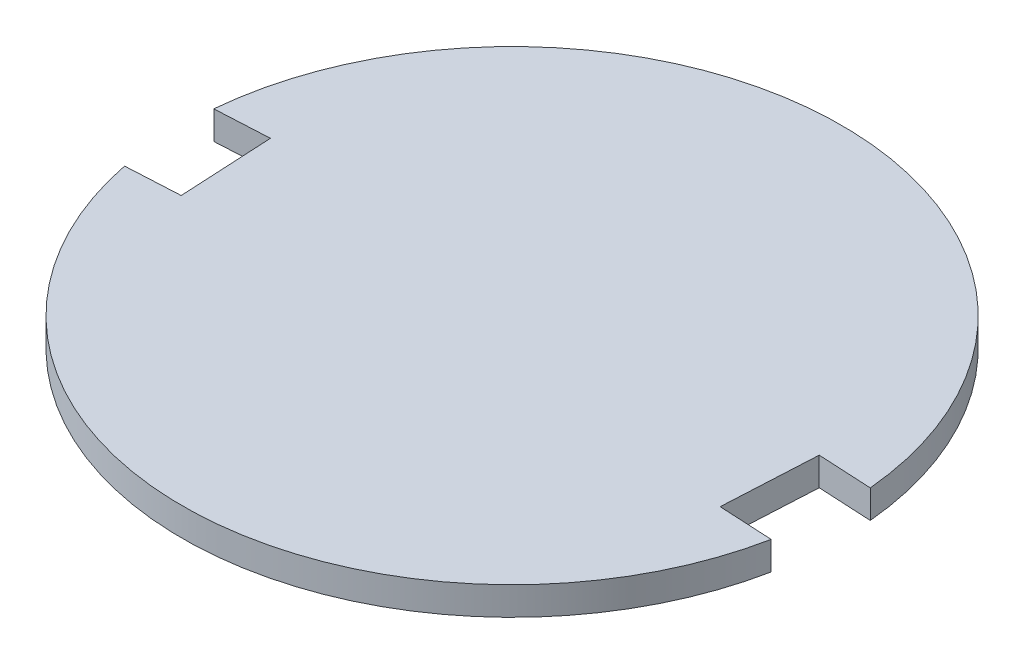
SolidWorks part; units mm, degrees
ref_plane "Спереди" through (0, 0, 0) normal (0, 0, 1) x (1, 0, 0)
ref_plane "Сверху" through (0, 0, 0) normal (0, 1, 0) x (1, 0, 0)
ref_plane "Справа" through (0, 0, 0) normal (1, 0, 0) x (0, 0, -1)
sketch "Эскиз1" plane through (0, 0, 0) normal (0, 1, 0) x (1, 0, 0)
  line L0 (-32.059, 10.3198) -> (-26.3445, 10.6193)
  line L1 (-26.3445, 10.6193) -> (-26.8686, 20.6193)
  line L2 (-26.8686, 20.6193) -> (-32.5851, 20.3197)
  line L3 (-32.6945, 17.1395) -> (-32.5029, 13.4847) construction
  line L4 (2.2701, 17.1395) -> (2.2701, 49.4493) construction
  line L5 (-32.5987, 15.3121) -> (2.2701, 17.1395) construction
  line L6 (36.5993, 10.3198) -> (30.8848, 10.6193)
  line L7 (30.8848, 10.6193) -> (31.4089, 20.6193)
  line L8 (31.4089, 20.6193) -> (37.1254, 20.3197)
  arc A0 (-32.059, 10.3198) -> (36.5993, 10.3198) centre (2.2701, 17.1395) ccw
  arc A1 (37.1254, 20.3197) -> (-32.5851, 20.3197) centre (2.2701, 17.1395) ccw
  point P14 (0, 0)
  dimension "D1" = 70
  dimension "D2" = 5
  dimension "D3" = 10
  dimension "D4" = 6
extrude "Бобышка-Вытянуть1" add sketch "Эскиз1" along normal blind 3
